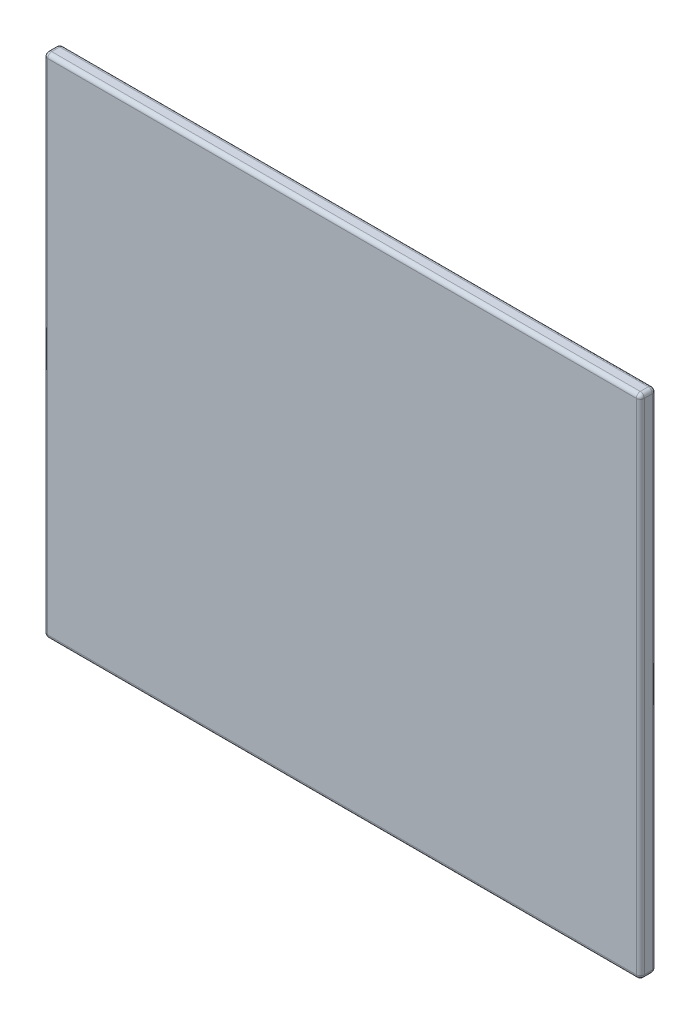
SolidWorks part; units mm, degrees
ref_plane "Front Plane" through (0, 0, 0) normal (0, 0, 1) x (1, 0, 0)
ref_plane "Top Plane" through (0, 0, 0) normal (0, 1, 0) x (1, 0, 0)
ref_plane "Right Plane" through (0, 0, 0) normal (1, 0, 0) x (0, 0, -1)
sketch "Sketch1" plane through (0, 0, 0) normal (0, 0, 1) x (1, 0, 0)
  line L1 (-37.35, -31.75) -> (37.35, -31.75)
  line L2 (-37.35, -31.75) -> (-37.35, 31.75)
  line L3 (-37.35, 31.75) -> (37.35, 31.75)
  line L4 (37.35, -31.75) -> (37.35, 31.75)
  line L5 (-37.35, -31.75) -> (37.35, 31.75) construction
  line L6 (-37.35, 31.75) -> (37.35, -31.75) construction
  point P0 (0, 0)
  dimension "D1" = 74.7
  dimension "D2" = 63.5
extrude "Boss-Extrude1" add sketch "Sketch1" along normal blind 2
fillet "Fillet1" radius 0.5 12 edges at (0, -31.75, 2) (0, -31.75, 0) (-37.35, 0, 2) (-37.35, -31.75, 1) (-37.35, 0, 0) (0, 31.75, 2) (-37.35, 31.75, 1) (0, 31.75, 0) (37.35, -31.75, 1) (37.35, 0, 2) (37.35, 31.75, 1) (37.35, 0, 0)
